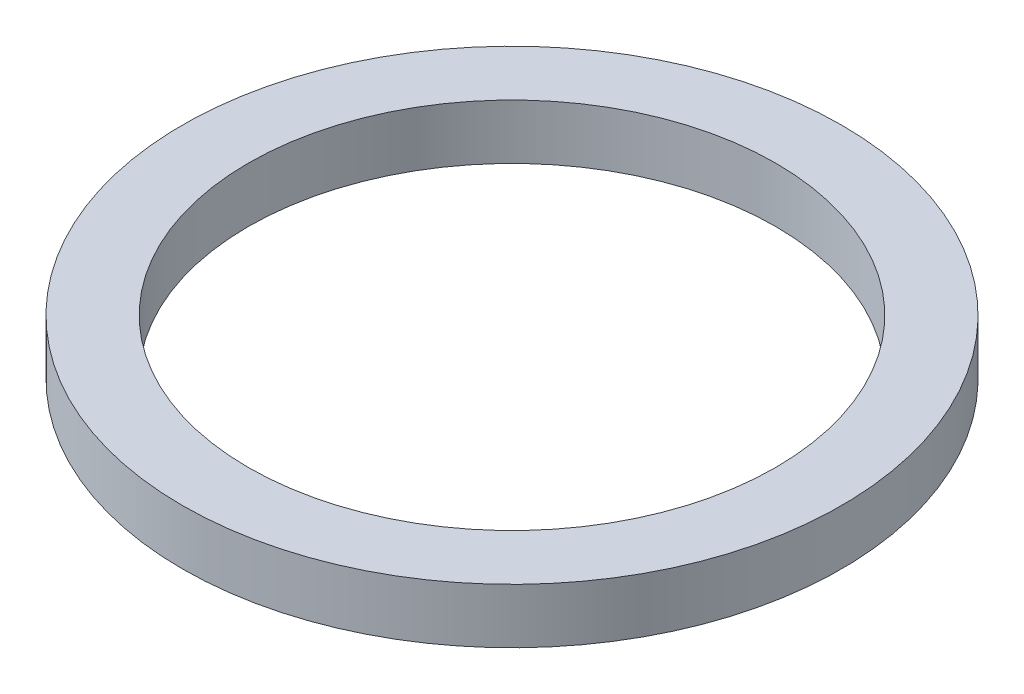
SolidWorks part; units mm, degrees
ref_plane "Front" through (0, 0, 0) normal (0, 0, 1) x (1, 0, 0)
ref_plane "Top" through (0, 0, 0) normal (0, 1, 0) x (1, 0, 0)
ref_plane "Right" through (0, 0, 0) normal (1, 0, 0) x (0, 0, -1)
sketch "Sketch1" plane through (0, 0, 0) normal (0, 1, 0) x (1, 0, 0)
  circle A0 centre (0, 0) radius 30
  circle A1 centre (0, 0) radius 24
extrude "Boss-Extrude1" add sketch "Sketch1" along normal blind 5
